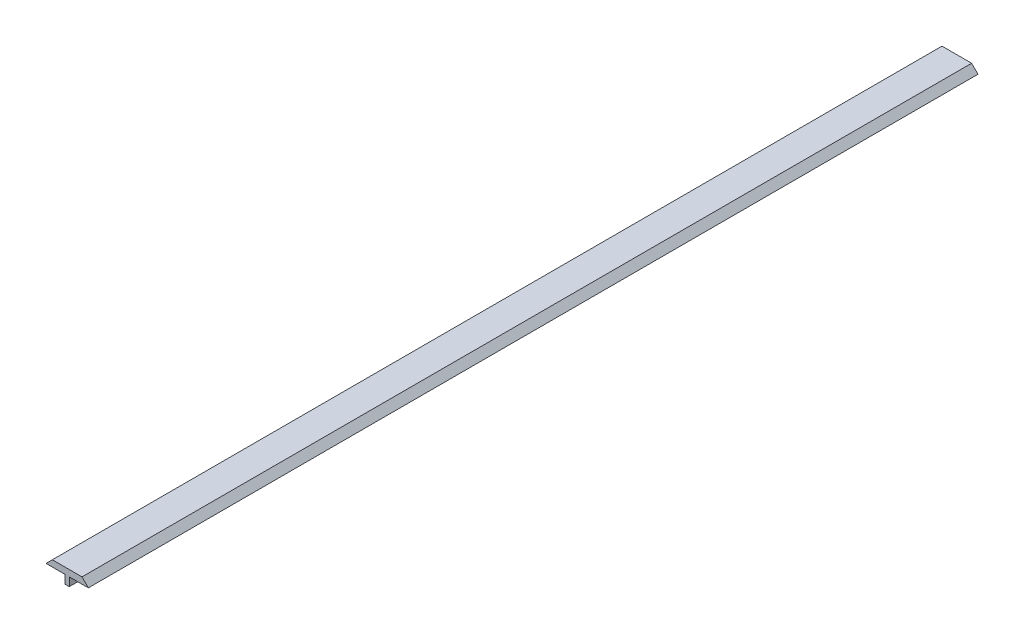
SolidWorks part; units mm, degrees
material "PET"
ref_plane "Front Plane" through (0, 0, 0) normal (0, 0, 1) x (1, 0, 0)
ref_plane "Top Plane" through (0, 0, 0) normal (0, 1, 0) x (1, 0, 0)
ref_plane "Right Plane" through (0, 0, 0) normal (1, 0, 0) x (0, 0, -1)
sketch "Sketch1" plane through (0, 0, 0) normal (0, 0, 1) x (1, 0, 0)
  line L0 (0, 0) -> (1, 0)
  line L1 (1, 0) -> (1, 2)
  line L2 (1, 2) -> (5.5, 2)
  line L3 (5.5, 2) -> (4, 3.5)
  line L4 (4, 3.5) -> (-3, 3.5)
  line L5 (-3, 3.5) -> (-4.5, 2)
  line L6 (-4.5, 2) -> (0, 2)
  line L7 (0, 2) -> (0, 0)
  dimension "D1" = 10
  dimension "D2" = 1
  dimension "D3" = 2
  dimension "D4" = 1.5
extrude "cover_connector" add sketch "Sketch1" along normal blind 210
